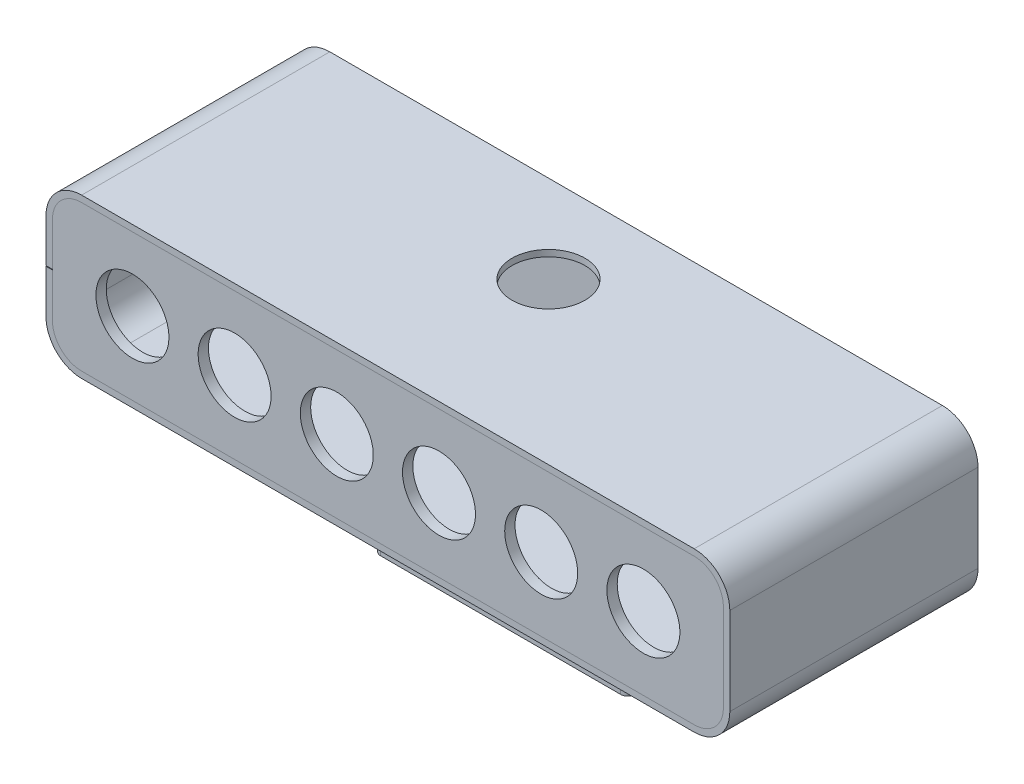
SolidWorks part; units mm, degrees
material "Acrylic (Medium-high impact)"
ref_plane "Front" through (0, 0, 0) normal (0, 0, 1) x (1, 0, 0)
ref_plane "Top" through (0, 0, 0) normal (0, 1, 0) x (1, 0, 0)
ref_plane "Right" through (0, 0, 0) normal (1, 0, 0) x (0, 0, -1)
sketch "Sketch5" plane through (0, 0, 0) normal (0, 1, 0) x (1, 0, 0)
  line L1 (0, 0) -> (-692.15, 0)
  line L2 (0, 0) -> (0, 107.95)
  line L3 (0, 107.95) -> (-692.15, 107.95)
  line L4 (-692.15, 0) -> (-692.15, 107.95)
  dimension "D1" = 107.95
  dimension "D2" = 692.15
extrude "Boss-Extrude4" [suppressed] add sketch "Sketch5" along normal blind 2.794
sketch "Sketch1" plane through (0, 0, 0) normal (0, 0, 1) x (1, 0, 0)
  line L1 (-145.923, 31.75) -> (145.923, 31.75)
  line L2 (-145.923, 31.75) -> (-145.923, -31.75)
  line L3 (-145.923, -31.75) -> (145.923, -31.75)
  line L4 (145.923, 31.75) -> (145.923, -31.75)
  line L5 (-145.923, 31.75) -> (145.923, -31.75) construction
  line L6 (-145.923, -31.75) -> (145.923, 31.75) construction
  point P0 (0, 0)
  dimension "D1" = 291.846
  dimension "D2" = 63.5
extrude "Boss-Extrude1" add sketch "Sketch1" along normal blind 4.4958
fillet "Fillet1" radius 12.7 4 edges at (-145.923, -31.75, 2.2479) (145.923, -31.75, 2.2479) (145.923, 31.75, 2.2479) (-145.923, 31.75, 2.2479)
sketch "Sketch3" plane through (0, 0, 0) normal (0, 0, 1) x (1, 0, 0)
  line L0 (133.223, 34.544) -> (-133.223, 34.544)
  line L1 (-148.717, 19.05) -> (-148.717, 0.254)
  line L2 (-133.223, -34.544) -> (133.223, -34.544)
  line L3 (148.717, -19.05) -> (148.717, 19.05)
  line L4 (-133.223, -31.75) -> (133.223, -31.75)
  line L5 (-145.923, 19.05) -> (-145.923, -19.05)
  line L6 (133.223, 31.75) -> (-133.223, 31.75)
  line L7 (145.923, -19.05) -> (145.923, 19.05)
  line L8 (-133.223, -31.75) -> (133.223, -31.75)
  line L9 (-145.923, 19.05) -> (-145.923, 0.254)
  line L10 (133.223, 31.75) -> (-133.223, 31.75)
  line L11 (145.923, -19.05) -> (145.923, 19.05)
  line L12 (-145.923, 0) -> (-148.717, 0)
  line L13 (-145.923, 0.254) -> (-148.717, 0.254)
  line L14 (-145.923, 0) -> (-145.923, -19.05)
  line L15 (-145.923, 19.05) -> (-145.923, -19.05) construction
  line L16 (-148.717, 0) -> (-148.717, -19.05)
  line L17 (-148.717, 19.05) -> (-148.717, -19.05) construction
  line L18 (-145.923, 19.05) -> (-145.923, -19.05) construction
  arc A0 (-133.223, 34.544) -> (-148.717, 19.05) centre (-133.223, 19.05) ccw
  arc A1 (-148.717, -19.05) -> (-133.223, -34.544) centre (-133.223, -19.05) ccw
  arc A2 (133.223, -34.544) -> (148.717, -19.05) centre (133.223, -19.05) ccw
  arc A3 (148.717, 19.05) -> (133.223, 34.544) centre (133.223, 19.05) ccw
  arc A4 (-145.923, -19.05) -> (-133.223, -31.75) centre (-133.223, -19.05) ccw
  arc A5 (-133.223, 31.75) -> (-145.923, 19.05) centre (-133.223, 19.05) ccw
  arc A6 (145.923, 19.05) -> (133.223, 31.75) centre (133.223, 19.05) ccw
  arc A7 (133.223, -31.75) -> (145.923, -19.05) centre (133.223, -19.05) ccw
  arc A8 (-145.923, -19.05) -> (-133.223, -31.75) centre (-133.223, -19.05) ccw
  arc A9 (-133.223, 31.75) -> (-145.923, 19.05) centre (-133.223, 19.05) ccw
  arc A10 (145.923, 19.05) -> (133.223, 31.75) centre (133.223, 19.05) ccw
  arc A11 (133.223, -31.75) -> (145.923, -19.05) centre (133.223, -19.05) ccw
  dimension "D3" = 0.254
  dimension "D1" = 0
  dimension "D2" = 2.794
extrude "Boss-Extrude2" add sketch "Sketch3" along normal blind 107.95 separate body
sketch "Sketch4" plane through (0, 0, 107.95) normal (0, 0, 1) x (1, 0, 0)
  line L4 (-145.923, 19.05) -> (-145.923, -19.05)
  line L5 (-133.223, -31.75) -> (133.223, -31.75)
  line L6 (145.923, -19.05) -> (145.923, 19.05)
  line L7 (133.223, 31.75) -> (-133.223, 31.75)
  line L8 (-145.923, 19.05) -> (-145.923, -19.05)
  line L9 (-133.223, -31.75) -> (133.223, -31.75)
  line L10 (145.923, -19.05) -> (145.923, 19.05)
  line L11 (133.223, 31.75) -> (-133.223, 31.75)
  arc A4 (-145.923, -19.05) -> (-133.223, -31.75) centre (-133.223, -19.05) ccw
  arc A5 (133.223, -31.75) -> (145.923, -19.05) centre (133.223, -19.05) ccw
  arc A6 (145.923, 19.05) -> (133.223, 31.75) centre (133.223, 19.05) ccw
  arc A7 (-133.223, 31.75) -> (-145.923, 19.05) centre (-133.223, 19.05) ccw
  arc A8 (-145.923, -19.05) -> (-133.223, -31.75) centre (-133.223, -19.05) ccw
  arc A9 (133.223, -31.75) -> (145.923, -19.05) centre (133.223, -19.05) ccw
  arc A10 (145.923, 19.05) -> (133.223, 31.75) centre (133.223, 19.05) ccw
  arc A11 (-133.223, 31.75) -> (-145.923, 19.05) centre (-133.223, 19.05) ccw
  dimension "D1" = 0
extrude "Boss-Extrude3" add sketch "Sketch4" against normal blind 4.4958 separate body
sketch "Sketch2" plane through (0, 0, 0) normal (0, 0, -1) x (-1, 0, 0)
  line L0 (22.225, 0) -> (-22.225, 0) construction
  line L1 (22.225, 0) -> (66.675, 0) construction
  line L2 (66.675, 0) -> (111.125, 0) construction
  line L3 (-22.225, 0) -> (-66.675, 0) construction
  line L4 (-66.675, 0) -> (-111.125, 0) construction
  line L5 (-111.125, 0) -> (-127, 0) construction
  line L6 (111.125, 0) -> (127, 0) construction
  circle A0 centre (-111.125, 0) radius 15.875
  circle A1 centre (-66.675, 0) radius 15.875
  circle A2 centre (-22.225, 0) radius 15.875
  circle A3 centre (22.225, 0) radius 15.875
  circle A4 centre (66.675, 0) radius 15.875
  circle A5 centre (111.125, 0) radius 15.875
  dimension "D1" = 31.75
  dimension "D2" = 254
extrude "Cut-Extrude1" cut sketch "Sketch2" against normal through all
sketch "Sketch6" plane through (0, -34.544, 0) normal (0, -1, 0) x (1, 0, 0)
  line L0 (0, 0) -> (0, 31.369) construction
  line L1 (-133.223, 0) -> (133.223, 0) construction
  line L2 (-52.705, 55.928) -> (-52.705, 6.81)
  line L3 (-52.245, 58.928) -> (52.245, 58.928)
  line L4 (-55.245, 55.928) -> (-55.245, 6.81)
  line L5 (-52.245, 3.81) -> (52.245, 3.81)
  line L6 (55.245, 55.928) -> (55.245, 6.81)
  line L7 (-55.245, 58.928) -> (55.245, 3.81) construction
  line L8 (-55.245, 3.81) -> (55.245, 58.928) construction
  line L9 (-52.245, 6.35) -> (52.245, 6.35)
  line L10 (52.705, 55.928) -> (52.705, 6.81)
  line L11 (-52.245, 56.388) -> (52.245, 56.388)
  arc A0 (-55.245, 6.81) -> (-52.245, 3.81) centre (-52.245, 6.81) ccw
  arc A1 (55.245, 6.81) -> (52.245, 3.81) centre (52.245, 6.81) cw
  arc A2 (55.245, 55.928) -> (52.245, 58.928) centre (52.245, 55.928) ccw
  arc A3 (-52.245, 58.928) -> (-55.245, 55.928) centre (-52.245, 55.928) ccw
  arc A4 (-52.705, 6.81) -> (-52.245, 6.35) centre (-52.245, 6.81) ccw
  arc A5 (52.705, 6.81) -> (52.245, 6.35) centre (52.245, 6.81) cw
  arc A6 (52.705, 55.928) -> (52.245, 56.388) centre (52.245, 55.928) ccw
  arc A7 (-52.245, 56.388) -> (-52.705, 55.928) centre (-52.245, 55.928) ccw
  dimension "D4" = 3
  dimension "D1" = 110.49
  dimension "D2" = 55.118
  dimension "D3" = 3.81
  dimension "D5" = 2.54
extrude "Boss-Extrude5" add sketch "Sketch6" along normal blind 50.8 separate body
sketch "Sketch7" plane through (0, 0, 0) normal (0, 0, -1) x (-1, 0, 0)
  line L0 (0, 0) -> (-52.3875, 0) construction
  line L1 (0, 0) -> (52.3875, 0) construction
  circle A0 centre (-52.3875, 0) radius 3.175
  circle A1 centre (52.3875, 0) radius 3.175
  dimension "D1" = 6.35
  dimension "D2" = 104.775
extrude "Cut-Extrude2" cut sketch "Sketch7" against normal up to next (4.4958 mm away)
sketch "Sketch8" plane through (0, -34.544, 0) normal (0, -1, 0) x (1, 0, 0)
  line L0 (0, 3.81) -> (0, 58.928) construction
  line L1 (-52.245, 3.81) -> (52.245, 3.81) construction
  line L2 (52.245, 58.928) -> (-52.245, 58.928) construction
  line L4 (-46.355, 53.594) -> (46.355, 53.594)
  line L5 (-50.165, 49.784) -> (-50.165, 12.954)
  line L6 (-46.355, 9.144) -> (46.355, 9.144)
  line L7 (50.165, 49.784) -> (50.165, 12.954)
  line L8 (-50.165, 53.594) -> (50.165, 9.144) construction
  line L9 (-50.165, 9.144) -> (50.165, 53.594) construction
  arc A0 (-50.165, 12.954) -> (-46.355, 9.144) centre (-46.355, 12.954) ccw
  arc A1 (50.165, 12.954) -> (46.355, 9.144) centre (46.355, 12.954) cw
  arc A2 (50.165, 49.784) -> (46.355, 53.594) centre (46.355, 49.784) ccw
  arc A3 (-46.355, 53.594) -> (-50.165, 49.784) centre (-46.355, 49.784) ccw
  point P6 (0, 31.369)
  dimension "D3" = 3.81
  dimension "D1" = 100.33
  dimension "D2" = 44.45
extrude "Cut-Extrude3" cut sketch "Sketch8" against normal up to next (2.794 mm away)
sketch "Sketch9" plane through (0, -34.544, 0) normal (0, -1, 0) x (1, 0, 0)
  line L2 (0, 0) -> (0, 38.1) construction
  circle A0 centre (0, 38.1) radius 15.875
  dimension "D1" = 31.75
  dimension "D2" = 38.1
extrude "Cut-Extrude4" cut sketch "Sketch9" against normal through all from surface at -66.294 starting at face at (0, 31.75, 53.975)
sketch "Sketch10" plane through (0, -34.544, 0) normal (0, -1, 0) x (1, 0, 0)
  circle A0 centre (63.5, 50.8) radius 1.7463
  circle A1 centre (63.5, 12.7) radius 1.7463
  circle A2 centre (-63.5, 50.8) radius 1.7462
  circle A3 centre (-63.5, 12.7) radius 1.7462
  arc A5 (-61.7042, 48.1817) -> (-60.3345, 51.046) centre (-63.5, 50.8) ccw construction
  arc A6 (-63.8073, 9.5399) -> (-60.9169, 10.8538) centre (-63.5, 12.7) ccw construction
  circle A7 centre (63.5, 50.8) radius 1.4732 construction
  circle A8 centre (63.5, 12.7) radius 1.4732 construction
  dimension "D1" = 3.4925
extrude "Cut-Extrude5" cut sketch "Sketch10" against normal up to next (2.794 mm away)
sketch "Sketch11" [suppressed] plane through (0, -31.75, 0) normal (0, 1, 0) x (1, 0, 0)
  line L0 (-133.223, -107.95) -> (-133.223, 0) construction
  line L1 (-133.223, -107.95) -> (-133.223, 0)
  line L2 (133.223, -107.95) -> (133.223, 0) construction
  line L3 (133.223, -107.95) -> (133.223, 0)
  line L4 (133.223, -107.95) -> (148.717, -107.95)
  line L5 (148.717, -107.95) -> (148.717, 0)
  line L6 (148.717, 0) -> (133.223, 0)
  line L7 (-133.223, 0) -> (-148.717, 0)
  line L8 (-148.717, 0) -> (-148.717, -107.95)
  line L9 (-148.717, -107.95) -> (-133.223, -107.95)
extrude "Cut-Extrude6" [suppressed] cut sketch "Sketch11" along normal through all
sketch "Sketch12" [suppressed] plane through (0, -31.75, 0) normal (0, 1, 0) x (1, 0, 0)
  line L0 (-133.223, -107.95) -> (-133.223, 0) construction
  line L1 (-133.223, -107.95) -> (-133.223, 0)
  line L2 (133.223, -107.95) -> (133.223, 0) construction
  line L3 (133.223, -107.95) -> (133.223, 0)
  line L4 (-142.0985, 0) -> (-142.0985, -107.95) construction
  line L5 (142.0985, 0) -> (-142.0985, 0) construction
  line L6 (142.0985, -107.95) -> (142.0985, 0) construction
  line L7 (142.0985, -107.95) -> (-142.0985, -107.95) construction
  line L8 (-142.0985, 0) -> (-142.0985, -107.95)
  line L9 (142.0985, 0) -> (133.223, 0)
  line L10 (142.0985, -107.95) -> (142.0985, 0)
  line L11 (142.0985, -107.95) -> (133.223, -107.95)
  line L12 (-133.223, -107.95) -> (-142.0985, -107.95)
  line L13 (-133.223, 0) -> (-142.0985, 0)
extrude "Cut-Extrude7" [suppressed] cut sketch "Sketch12" against normal through all
sketch "Sketch13" [suppressed] plane through (0, 34.544, 0) normal (0, 1, 0) x (1, 0, 0)
  line L4 (133.223, 0) -> (-133.223, 0)
  line L5 (-133.223, 0) -> (-133.223, -107.95)
  line L6 (-133.223, -107.95) -> (133.223, -107.95)
  line L7 (133.223, -107.95) -> (133.223, 0)
  line L8 (133.223, 0) -> (-133.223, 0)
  line L9 (-133.223, 0) -> (-133.223, -107.95)
  line L10 (-133.223, -107.95) -> (133.223, -107.95)
  line L11 (133.223, -107.95) -> (133.223, 0)
  dimension "D1" = 0
extrude "Cut-Extrude8" [suppressed] cut sketch "Sketch13" against normal up to surface (2.794 mm away)
sketch "Sketch14" [suppressed] plane through (0, -31.75, 0) normal (0, 1, 0) x (1, 0, 0)
  line L1 (-133.223, -107.95) -> (-171.323, -107.95)
  line L2 (-133.223, -107.95) -> (-133.223, 0)
  line L3 (-133.223, 0) -> (-171.323, 0)
  line L4 (-171.323, -107.95) -> (-171.323, 0)
  dimension "D1" = 38.1
sketch "Sketch15" [suppressed] plane through (0, -31.75, 0) normal (0, 1, 0) x (1, 0, 0)
  line L0 (-133.223, -107.95) -> (-133.223, 0) construction
  line L1 (133.223, -107.95) -> (558.927, -107.95)
  line L2 (133.223, -107.95) -> (133.223, 0)
  line L3 (133.223, 0) -> (558.927, 0)
  line L4 (558.927, -107.95) -> (558.927, 0)
  dimension "D1" = 692.15
extrude "Boss-Extrude6" [suppressed] add sketch "Sketch15" against normal up to surface (2.794 mm away)
